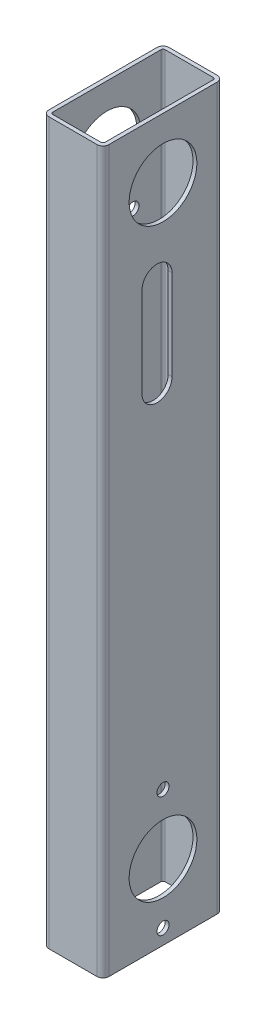
SolidWorks part; units mm, degrees
material "6061-T6 (SS)"
ref_plane "Front Plane" through (0, 0, 0) normal (0, 0, 1) x (1, 0, 0)
ref_plane "Top Plane" through (0, 0, 0) normal (0, 1, 0) x (1, 0, 0)
ref_plane "Right Plane" through (0, 0, 0) normal (1, 0, 0) x (0, 0, -1)
sketch "Sketch1" plane through (0, 0, 0) normal (0, 1, 0) x (1, 0, 0)
  line L1 (10.16, -25.4) -> (-10.16, -25.4)
  line L2 (12.7, -22.86) -> (12.7, 22.86)
  line L3 (10.16, 25.4) -> (-10.16, 25.4)
  line L4 (-12.7, -22.86) -> (-12.7, 22.86)
  line L5 (12.7, -25.4) -> (-12.7, 25.4) construction
  line L6 (12.7, 25.4) -> (-12.7, -25.4) construction
  arc A0 (-10.16, -25.4) -> (-12.7, -22.86) centre (-10.16, -22.86) cw
  arc A1 (10.16, -25.4) -> (12.7, -22.86) centre (10.16, -22.86) ccw
  arc A2 (12.7, 22.86) -> (10.16, 25.4) centre (10.16, 22.86) ccw
  arc A3 (-10.16, 25.4) -> (-12.7, 22.86) centre (-10.16, 22.86) ccw
  point P0 (0, 0)
  dimension "D3" = 2.54
  dimension "D1" = 25.4
  dimension "D2" = 50.8
extrude "Extrude-Thin1" add sketch "Sketch1" along normal blind 222.25 and the other way blind 82.55 thin
sketch "Sketch2" plane through (-12.7, 0, 0) normal (-1, 0, 0) x (0, 0, 1)
  line L0 (2.54, 161.9426) -> (2.54, 12.7) construction
  line L4 (9.2075, 161.9426) -> (9.2075, 12.7)
  line L5 (-4.1275, 161.9426) -> (-4.1275, 12.7)
  line L6 (2.54, 25.4) -> (2.54, 149.2426) construction
  arc A2 (9.2075, 161.9426) -> (-4.1275, 161.9426) centre (2.54, 161.9426) ccw
  arc A3 (-4.1275, 12.7) -> (9.2075, 12.7) centre (2.54, 12.7) ccw
  point P3 (2.54, 87.3213)
  dimension "D5" = 13.335
  dimension "D2" = 12.7
  dimension "D1" = 12.7
extrude "Cut-Extrude1" cut sketch "Sketch2" against normal up to next
sketch "Sketch5" plane through (12.7, 0, 0) normal (1, 0, 0) x (0, 0, -1)
  line L0 (-2.54, 161.9426) -> (-2.54, 123.8426) construction
  line L1 (3.81, 161.9426) -> (3.81, 123.8426)
  line L2 (-8.89, 161.9426) -> (-8.89, 123.8426)
  arc A0 (3.81, 161.9426) -> (-8.89, 161.9426) centre (-2.54, 161.9426) ccw
  arc A1 (-8.89, 123.8426) -> (3.81, 123.8426) centre (-2.54, 123.8426) ccw
  arc A2 (4.1275, 161.9426) -> (-9.2075, 161.9426) centre (-2.54, 161.9426) ccw construction
  point P2 (-2.54, 142.8926)
  dimension "D1" = 6.35
  dimension "D2" = 38.1
extrude "Cut-Extrude4" cut sketch "Sketch5" against normal up to next
sketch "Sketch4" plane through (-12.7, 0, 0) normal (1, 0, 0) x (0, 0, -1)
  circle A12 centre (11.049, 4.7713) radius 2.5527
  circle A13 centre (-16.129, 4.7713) radius 2.5527
  circle A14 centre (-16.129, 87.3213) radius 2.5527
  circle A15 centre (11.049, 87.3213) radius 2.5527
  circle A16 centre (-16.129, 169.8713) radius 2.5527
  circle A17 centre (11.049, 169.8713) radius 2.5527
  dimension "D1" = 5.1054
extrude "Cut-Extrude3" cut sketch "Sketch4" along normal up to surface (1.651 mm away) up to face at (-11.049, 87.3213, 2.54)
sketch "Sketch6" plane through (12.7, 0, 0) normal (1, 0, 0) x (0, 0, -1)
  line L0 (25.4, -82.55) -> (25.4, 222.25) construction
  circle A0 centre (0, -50.8) radius 14.3256
  circle A1 centre (0, 196.85) radius 14.3256
  dimension "D1" = 28.6512
  dimension "D2" = 25.4
  dimension "D3" = 50.8
  dimension "D4" = 247.65
extrude "Cut-Extrude5" cut sketch "Sketch6" against normal through all
hole_wizard "#10 Clearance Hole1" positions "Sketch8" profile "Sketch9" hole size "#10" standard "ANSI Inch" end condition through all
sketch "Sketch8" plane through (12.7, 0, 0) normal (1, 0, 0) x (0, 0, -1)
  circle A0 centre (0, -50.8) radius 25.4 construction
  point P0 (0, -25.4)
  point P11 (0, -76.2)
  dimension "D1" = 50.8
sketch "Sketch9" plane through (12.7, -25.4, 0) normal (0, 1, 0) x (0, 0, -1)
  line L0 (0, 0) -> (0, 25.4)
  line L1 (0, 25.4) -> (2.5527, 25.4)
  line L2 (2.5527, 25.4) -> (2.5527, 0)
  line L5 (2.5527, 0) -> (0, 0)
  line L11 (0, -6.35) -> (0, 107.95) construction
  dimension "Thru Hole Dia." = 5.1054
  dimension "Thru Hole Depth" = 25.4
